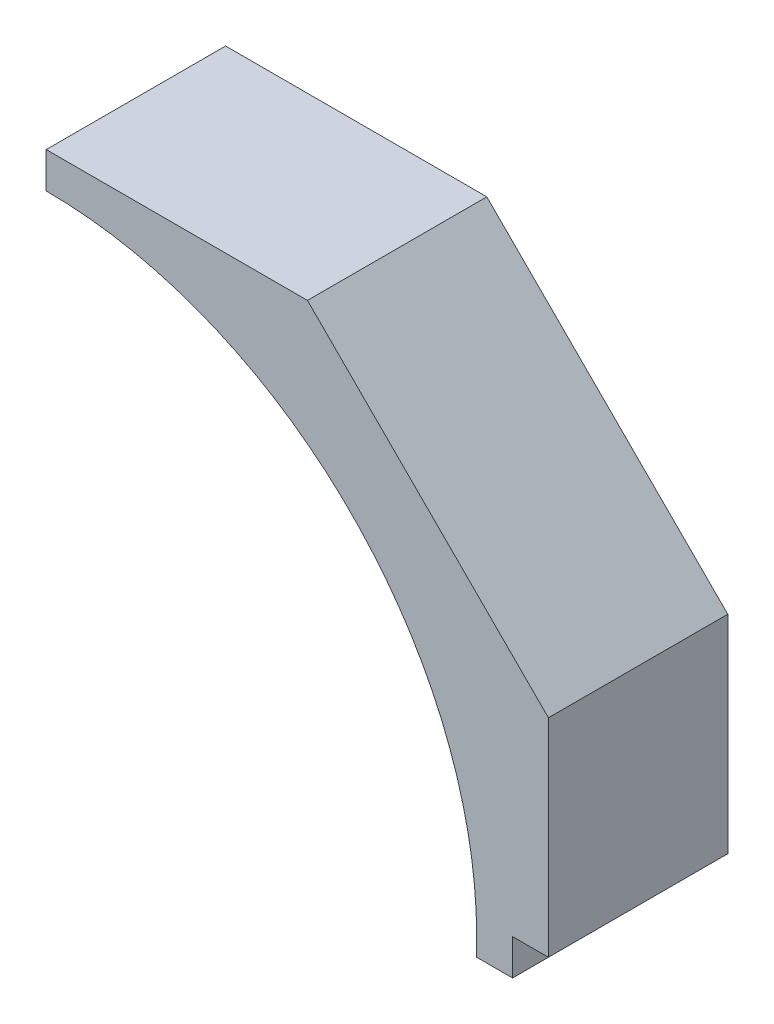
SolidWorks part; units mm, degrees
ref_plane "Front" through (0, 0, 0) normal (0, 0, 1) x (1, 0, 0)
ref_plane "Top" through (0, 0, 0) normal (0, 1, 0) x (1, 0, 0)
ref_plane "Right" through (0, 0, 0) normal (1, 0, 0) x (0, 0, -1)
sketch "Sketch2" plane through (0, 0, 0) normal (0, 0, 1) x (1, 0, 0)
  line L0 (0, 30.48) -> (0, 33.02)
  line L1 (0, 33.02) -> (18.4975, 33.02)
  line L2 (35.56, 15.9575) -> (35.56, 0) construction
  line L3 (35.56, 0) -> (30.48, 0) construction
  line L4 (18.4975, 33.02) -> (35.56, 15.9575)
  line L5 (30.48, 0) -> (30.48, -1.27)
  line L6 (30.48, -1.27) -> (35.56, -1.27)
  line L7 (35.56, 0) -> (35.56, -1.27) construction
  line L8 (38.1, -1.27) -> (35.56, -1.27)
  line L9 (38.1, -1.27) -> (35.56, 15.9575)
  circle A0 centre (0, 0) radius 2.54 construction
  circle A1 centre (0, 16.51) radius 13.97 construction
  arc A2 (0, 30.48) -> (30.48, 0) centre (0, 0) cw
  dimension "D1" = 5.08
  dimension "D2" = 27.94
  dimension "D3" = 5.08
  dimension "D4" = 2.54
  dimension "D5" = 24.13
  dimension "D6" = 135
  dimension "D7" = 1.27
  dimension "D8" = 2.54
extrude "Boss-Extrude2" add sketch "Sketch2" along normal blind 12.7
sketch "Sketch3" plane through (0, 0, 12.7) normal (0, 0, 1) x (1, 0, 0)
  line L0 (30.48, -1.27) -> (38.1, -1.27) construction
  line L1 (33.02, -1.27) -> (38.1, -1.27)
  line L2 (33.02, -1.27) -> (33.02, 24.13)
  line L3 (33.02, 24.13) -> (38.1, 24.13)
  line L4 (38.1, -1.27) -> (38.1, 24.13)
  dimension "D1" = 2.54
  dimension "D2" = 25.4
  dimension "D3" = 5.08
extrude "Cut-Extrude1" cut sketch "Sketch3" against normal through all
sketch "Sketch4" plane through (0, 0, 12.7) normal (0, 0, 1) x (1, 0, 0)
  line L0 (33.02, 18.4975) -> (33.02, -1.27) construction
  line L1 (33.02, 1.27) -> (35.56, 1.27)
  line L2 (33.02, 1.27) -> (33.02, 18.4975)
  line L4 (35.56, 1.27) -> (35.56, 15.9575)
  line L5 (30.48, -1.27) -> (33.02, -1.27) construction
  line L6 (33.02, 18.4975) -> (35.56, 15.9575)
  line L7 (33.02, 18.4975) -> (18.4975, 33.02) construction
  point P9 (0, 0)
  point P13 (0, 0)
  point P14 (0, 0)
  dimension "D1" = 2.54
  dimension "D2" = 2.54
extrude "Boss-Extrude3" add sketch "Sketch4" against normal up to surface (12.7 mm away) up to face at (21.6872, 16.97, 0)
